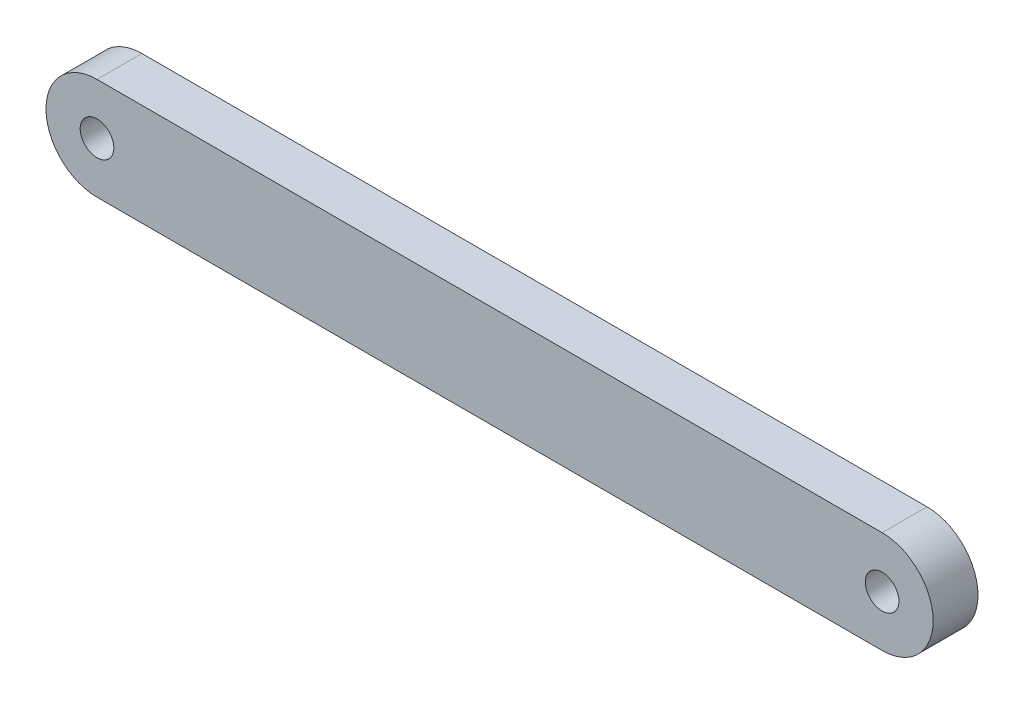
SolidWorks part; units mm, degrees
ref_plane "Front Plane" through (0, 0, 0) normal (0, 0, 1) x (1, 0, 0)
ref_plane "Top Plane" through (0, 0, 0) normal (0, 1, 0) x (1, 0, 0)
ref_plane "Right Plane" through (0, 0, 0) normal (1, 0, 0) x (0, 0, -1)
sketch "Sketch1" plane through (0, 0, 0) normal (0, 0, 1) x (1, 0, 0)
  line L0 (-17.2473, -0.8213) -> (17.7527, -0.8213) construction
  line L1 (-17.2473, 1.4531) -> (17.7527, 1.4531)
  line L2 (-17.2473, -3.0957) -> (17.7527, -3.0957)
  arc A0 (-17.2473, 1.4531) -> (-17.2473, -3.0957) centre (-17.2473, -0.8213) ccw
  arc A1 (17.7527, -3.0957) -> (17.7527, 1.4531) centre (17.7527, -0.8213) ccw
  circle A2 centre (-17.2473, -0.8213) radius 0.75
  circle A3 centre (17.7527, -0.8213) radius 0.75
  point P2 (0.2527, -0.8213)
  dimension "D1" = 35
extrude "Boss-Extrude1" add sketch "Sketch1" along normal blind 2
